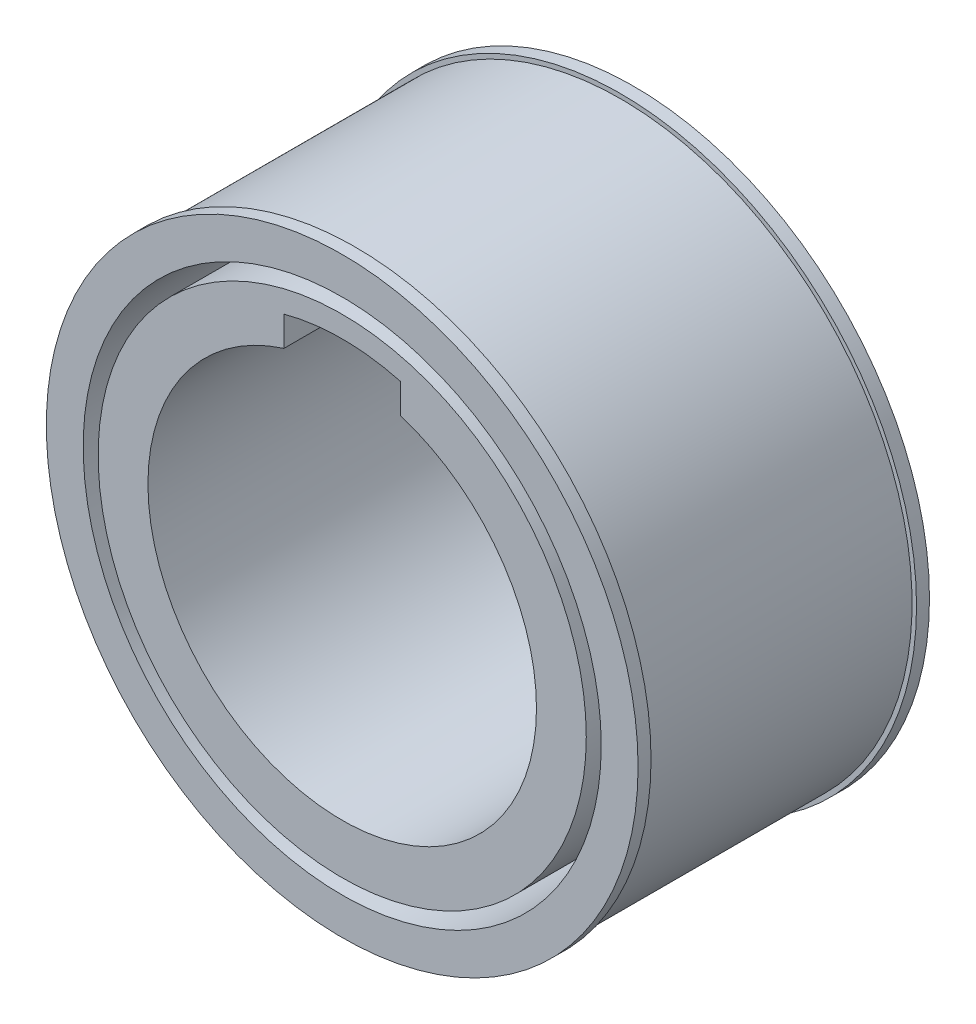
SolidWorks part; units mm, degrees
ref_plane "Front Plane" through (0, 0, 0) normal (0, 0, 1) x (1, 0, 0)
ref_plane "Top Plane" through (0, 0, 0) normal (0, 1, 0) x (1, 0, 0)
ref_plane "Right Plane" through (0, 0, 0) normal (1, 0, 0) x (0, 0, -1)
sketch "Sketch1" plane through (0, 0, 0) normal (0, 0, 1) x (1, 0, 0)
  circle A0 centre (0, 0) radius 45
  dimension "D1" = 90
extrude "Boss-Extrude1" add sketch "Sketch1" along normal mid plane 45
sketch "Sketch2" plane through (0, 0, 22.5) normal (0, 0, 1) x (1, 0, 0)
  circle A2 centre (0, 0) radius 45.69
  circle A3 centre (0, 0) radius 45.69
  dimension "D1" = 0.69
extrude "Boss-Extrude2" add sketch "Sketch2" against normal blind 2
mirror "Mirror1" about plane through (0, 0, 0) normal (0, 0, 1) of "Boss-Extrude2"
sketch "Sketch4" plane through (0, 0, 0) normal (0, 0, 1) x (1, 0, 0)
  circle A0 centre (0, 0) radius 40
  circle A1 centre (0, 0) radius 37.69
  circle A2 centre (0, 0) radius 45.69 construction
  dimension "D1" = 80
  dimension "D2" = 8
extrude "Cut-Extrude1" cut sketch "Sketch4" along normal blind 30
sketch "Sketch5" plane through (0, 0, 22.5) normal (0, 0, 1) x (1, 0, 0)
  circle A0 centre (0, 0) radius 30
  dimension "D1" = 60
extrude "Cut-Extrude2" cut sketch "Sketch5" against normal through all both and the other way through all
sketch "Sketch6" plane through (0, 0, 22.5) normal (0, 0, 1) x (1, 0, 0)
  line L0 (0, 0) -> (0, 50000) construction
  line L1 (9, 20.1741) -> (9, 33.2018)
  line L2 (-9, 20.1741) -> (-9, 33.2018)
  line L3 (-9, 20.1741) -> (9, 20.1741)
  line L4 (-9, 0) -> (-9, 50000) construction
  line L5 (9, 0) -> (9, 50000) construction
  arc A0 (9, 33.2018) -> (-9, 33.2018) centre (0, 0) ccw
  point P12 (0, 0)
  dimension "D3" = 34.4
  dimension "D4" = 20.1741
  dimension "D1" = 9
  dimension "D2" = 9
extrude "Cut-Extrude3" cut sketch "Sketch6" against normal through all
